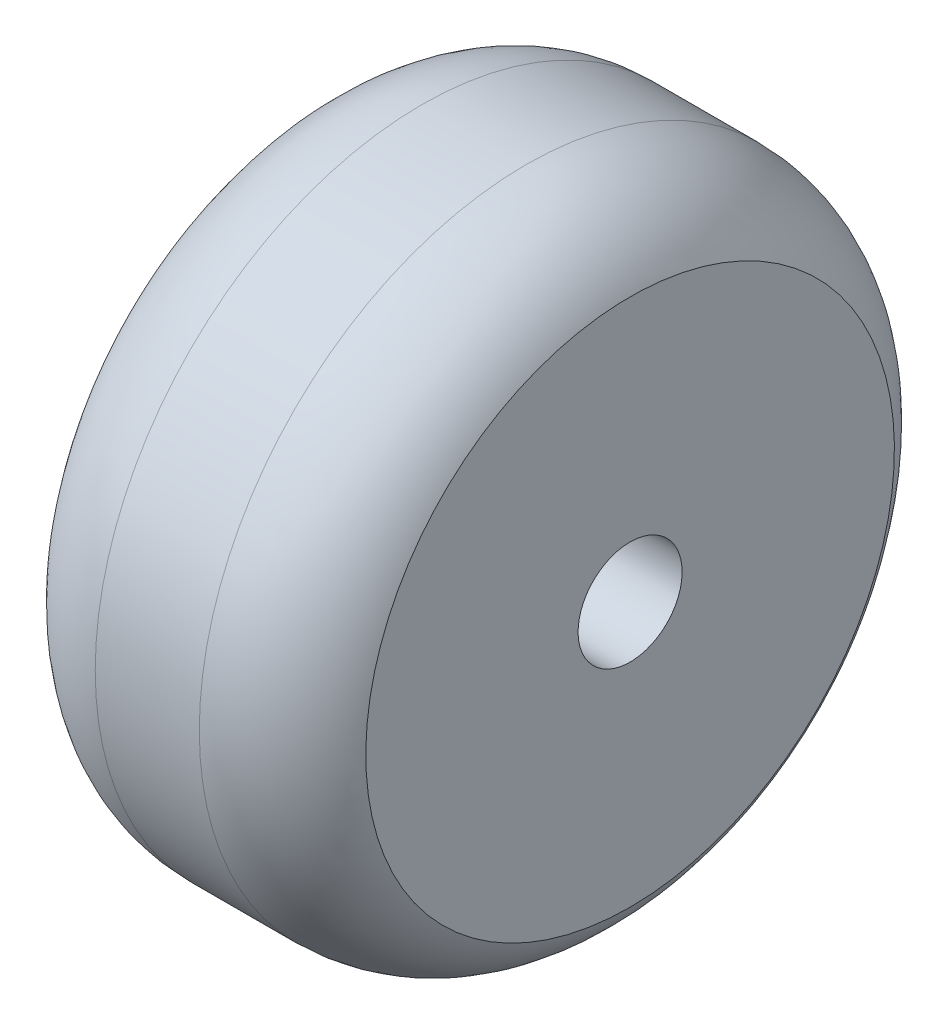
SolidWorks part; units mm, degrees
material "Silicon Rubber"
ref_plane "Front Plane" through (0, 0, 0) normal (0, 0, 1) x (1, 0, 0)
ref_plane "Top Plane" through (0, 0, 0) normal (0, 1, 0) x (1, 0, 0)
ref_plane "Right Plane" through (0, 0, 0) normal (1, 0, 0) x (0, 0, -1)
sketch "Sketch1" plane through (0, 0, 0) normal (0, 0, 1) x (1, 0, 0)
  line L0 (-9.525, 0) -> (9.525, 0)
  line L1 (0, 19.939) -> (0, -19.939) construction
  line L2 (-3.175, -19.939) -> (3.175, -19.939)
  line L3 (-9.525, -16.129) -> (-9.525, 16.129)
  line L4 (-3.175, 19.939) -> (3.175, 19.939)
  line L5 (9.525, -16.129) -> (9.525, 16.129)
  line L6 (-9.525, -19.939) -> (9.525, 19.939) construction
  line L7 (-9.525, 19.939) -> (9.525, -19.939) construction
  line L8 (-9.525, -19.939) -> (-9.525, -16.129) construction
  line L9 (-9.525, -19.939) -> (-3.175, -19.939) construction
  line L10 (3.175, -19.939) -> (9.525, -19.939) construction
  line L11 (9.525, -19.939) -> (9.525, -16.129) construction
  line L12 (9.525, 16.129) -> (9.525, 19.939) construction
  line L13 (3.175, 19.939) -> (9.525, 19.939) construction
  line L14 (-9.525, 19.939) -> (-3.175, 19.939) construction
  line L15 (-9.525, 16.129) -> (-9.525, 19.939) construction
  arc A0 (3.175, -19.939) -> (9.525, -16.129) centre (3.175, -12.7423) ccw
  arc A1 (-3.175, -19.939) -> (-9.525, -16.129) centre (-3.175, -12.7423) cw
  arc A2 (-9.525, 16.129) -> (-3.175, 19.939) centre (-3.175, 12.7423) cw
  arc A3 (3.175, 19.939) -> (9.525, 16.129) centre (3.175, 12.7423) cw
  point P3 (0, 0)
  point P4 (0, 0)
  dimension "D1" = 19.05
  dimension "D3" = 32.258
  dimension "D2" = 39.878
  dimension "D4" = 6.35
  dimension "D5" = 19.05
revolve "Revolve1" add sketch "Sketch1" angle 360 about L0
sketch "Sketch2" plane through (9.525, 0, 0) normal (1, 0, 0) x (0, 0, -1)
  circle A0 centre (0, 0) radius 3.175
  dimension "D1" = 6.35
extrude "Cut-Extrude1" cut sketch "Sketch2" against normal through all
